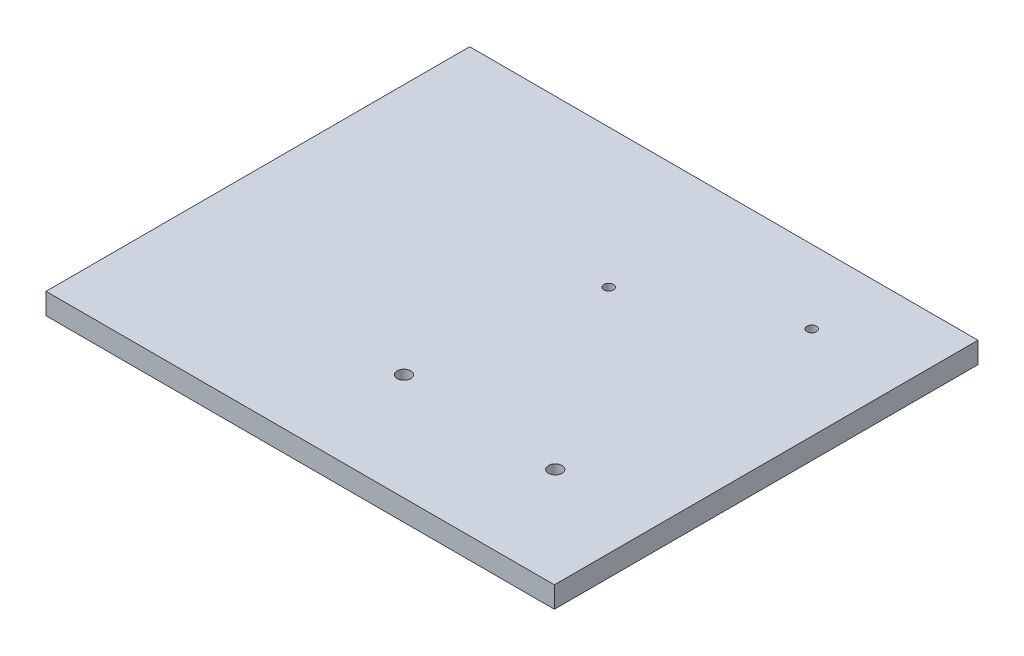
SolidWorks part; units mm, degrees
ref_plane "Front Plane" through (0, 0, 0) normal (0, 0, 1) x (1, 0, 0)
ref_plane "Top Plane" through (0, 0, 0) normal (0, 1, 0) x (1, 0, 0)
ref_plane "Right Plane" through (0, 0, 0) normal (1, 0, 0) x (0, 0, -1)
sketch "Sketch1" plane through (0, 0, 0) normal (0, 1, 0) x (1, 0, 0)
  line L0 (-66.0627, 0) -> (65.2437, 0) construction
  line L1 (-60, 50) -> (60, 50)
  line L2 (-60, 50) -> (-60, -50)
  line L3 (-60, -50) -> (60, -50)
  line L4 (60, 50) -> (60, -50)
  line L6 (40, -40) -> (-23.5, -40) construction
  line L7 (40, -40) -> (40, -15) construction
  line L8 (40, -15) -> (-23.5, -15) construction
  line L9 (-23.5, -40) -> (-23.5, -15) construction
  line L10 (-5.21, 35.09) -> (40, 35.09) construction
  line L11 (-5.21, 35.09) -> (-5.21, 15) construction
  line L12 (-5.21, 15) -> (40, 15) construction
  line L13 (40, 35.09) -> (40, 15) construction
  line L14 (-5.21, 35.09) -> (40, 15) construction
  line L15 (-5.21, 15) -> (40, 35.09) construction
  circle A0 centre (36.5, -26.3) radius 1.6
  circle A1 centre (-0.7, -24.8) radius 1.6
  circle A2 centre (38.07, 32.68) radius 1.13
  circle A3 centre (5.56, 17.26) radius 1.13
  point P4 (60, 0)
  point P6 (0, 50)
  point P23 (17.395, 25.045)
  dimension "D5" = 3.2
  dimension "D10" = 3.2
  dimension "D17" = 2.26
  dimension "D18" = 2.26
  dimension "D1" = 120
  dimension "D2" = 100
  dimension "D3" = 15
  dimension "D4" = 20
  dimension "D6" = 3.5
  dimension "D7" = 13.7
  dimension "D8" = 63.5
  dimension "D9" = 25
  dimension "D11" = 40.7
  dimension "D12" = 15.2
  dimension "D13" = 45.21
  dimension "D14" = 20.09
  dimension "D15" = 15
  dimension "D16" = 20
  dimension "D19" = 15.42
  dimension "D20" = 17.68
  dimension "D21" = 32.51
  dimension "D22" = 1.93
extrude "Boss-Extrude1" add sketch "Sketch1" along normal blind 5
